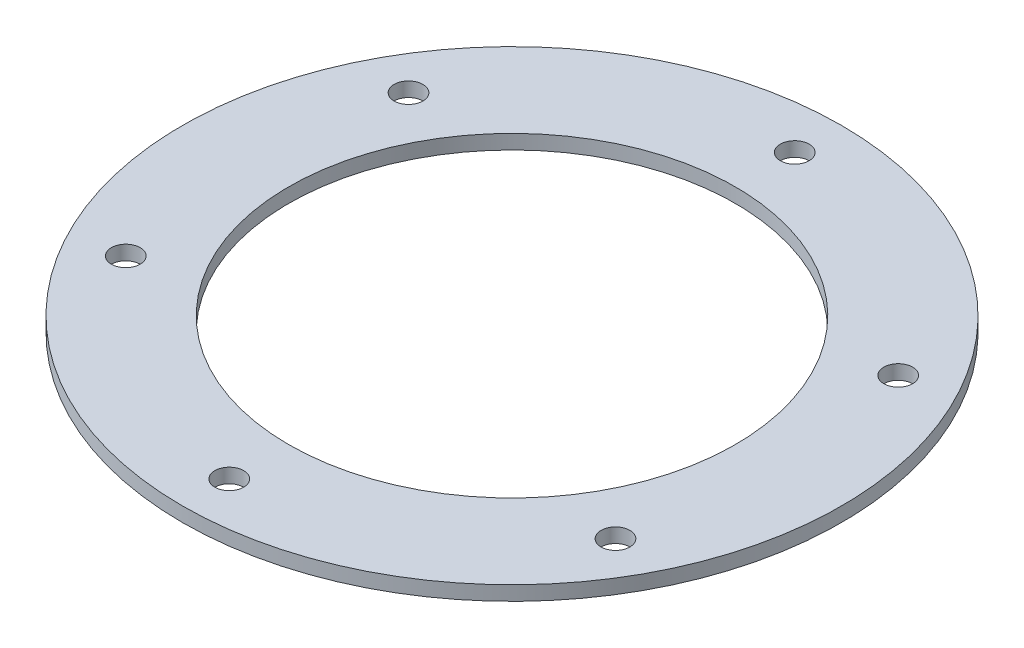
SolidWorks part; units mm, degrees
material "ABS"
ref_plane "Front Plane" through (0, 0, 0) normal (0, 0, 1) x (1, 0, 0)
ref_plane "Top Plane" through (0, 0, 0) normal (0, 1, 0) x (1, 0, 0)
ref_plane "Right Plane" through (0, 0, 0) normal (1, 0, 0) x (0, 0, -1)
sketch "Sketch1" plane through (0, 0, 0) normal (0, 1, 0) x (1, 0, 0)
  circle A0 centre (0, 0) radius 45.75
  circle A1 centre (0, 0) radius 31
  circle A2 centre (0, 0) radius 39.25 construction
  circle A3 centre (0, 39.25) radius 2
  circle A4 centre (33.9915, 19.625) radius 2
  circle A5 centre (33.9915, -19.625) radius 2
  circle A6 centre (0, -39.25) radius 2
  circle A7 centre (-33.9915, -19.625) radius 2
  circle A8 centre (-33.9915, 19.625) radius 2
  point P19 (0, 0)
  dimension "D1" = 91.5
  dimension "D2" = 62
  dimension "D3" = 78.5
  dimension "D4" = 4
  dimension "D5" = 6
extrude "Boss-Extrude1" add sketch "Sketch1" against normal mid plane 2
equation "\"Ns\" = 33"
equation "\"Np\" = 45"
equation "\"Nr\" = 123"
equation "\"num_planet\" = 3"
equation "\"module\" = 0.5"
equation "\"pressure angle\" = 20.0"
equation "\"motor_mount_hole_PCD\" = 32"
equation "\"motor_mount_hole_dia\" = 4"
equation "\"motor_mount_hole_num\" = 4"
equation "\"motor_output_hole_PCD\" = 22"
equation "\"motor_output_hole_dia\" = 3"
equation "\"motor_output_hole_num\" = 4"
equation "\"motor_OD\" = 72"
equation "\"motor_height\" = 27"
equation "\"wire_slot_dist_from_center\" = 30"
equation "\"wire_slot_length\" = 10"
equation "\"wire_slot_radius\" = 2.5"
equation "\"h_a\" = 0.5"
equation "\"h_b\" = 0.625"
equation "\"clr_tip_root\" = 0.125"
equation "\"dp_s\" = 16.5"
equation "\"db_s\" = 15.50492824296749"
equation "\"fw_s_calc\" = 1.2595130854287364"
equation "\"alpha_s\" = 0.8539582918412449"
equation "\"beta_s\" = 3.7466288708629643"
equation "\"dp_p\" = 22.5"
equation "\"db_p\" = 21.14308396768294"
equation "\"fw_p\" = 8.0"
equation "\"alpha_p\" = 0.8539582918412307"
equation "\"beta_p\" = 2.2920834163175385"
equation "\"pressure_angle\" = 20.0"
equation "\"h_f\" = 0.625"
equation "\"dp_r\" = 61.5"
equation "\"db_r\" = 57.79109617833337"
equation "\"fw_r\" = 8.0"
equation "\"alpha_r\" = 0.8539582918412414"
equation "\"beta_r\" = 3.171331217828824"
equation "\"bearing_ID\" = 50"
equation "\"bearing_OD\" = 65"
equation "\"bearing_height\" = 7"
equation "\"clearance_planet\" = 1.5"
equation "\"case_dist\" = 6.5"
equation "\"Motor_case_OD_max\" = 96.5"
equation "\"case_mounting_PCD\" = 89.0"
equation "\"bearing mount thickness\" = 8"
equation "\"case_mounting_hole_dia\" = 3"
equation "\"output_mounting_PCD\" = 73"
equation "\"output_mounting_hole_dia\" = 4"
equation "\"clearance_case_mount_holes_shell_thickness\" = 1"
equation "\"motor_case_OD_base\" = 87.0"
equation "\"sec_carrier_thickness\" = 5"
equation "\"sun_coupler_hub_thickness\" = 4"
equation "\"clearance_sun_coupler_sec_carrier\" = 1.5"
equation "\"clearance_motor_and_case\" = 5"
equation "\"Motor_case_thickness\" = 2.5"
equation "\"Motor_case_ID\" = 82"
equation "\"case_mounting_hole_shift\" = 1.0"
equation "\"output_mounting_nut_wrench_size\" = 7"
equation "\"output_mounting_nut_thickness\" = 3.2"
equation "\"case_mounting_hole_allen_socket_dia\" = 5.5"
equation "\"output_mounting_nut_depth\" = 3"
equation "\"case_mounting_bolt_depth\" = 4.5"
equation "\"ring_radial_thickness\" = 5"
equation "\"ring_OD\" = 71.5"
equation "\"ring_to_chamfer_clearance\" = 2"
equation "\"Motor_case_OD_base_to_chamfer\" = 5"
equation "\"pattern_offset_from_motor_case_OD_base\" = 3"
equation "\"pattern_bulge_dia\" = 3"
equation "\"pattern_num_bulge\" = 18"
equation "\"pattern_depth\" = 2"
equation "\"case_mounting_wrench_size\" = 5.5"
equation "\"case_mounting_nut_clearance\" = 2"
equation "\"base_plate_thickness\" = 4"
equation "\"case_mounting_nut_thickness\" = 2.4"
equation "\"case_mounting_surface_height\" = 4"
equation "\"central_hole_offset_from_motor_mount_PCD\" = 5"
equation "\"driver_upper_holes_dist_from_center\" = 23"
equation "\"driver_lower_holes_dist_from_center\" = 15"
equation "\"driver_side_holes_dist_from_center\" = 20"
equation "\"driver_mount_holes_dia\" = 2.5"
equation "\"driver_mount_inserts_OD\" = 3.5"
equation "\"driver_mount_thickness\" = 1.5"
equation "\"driver_mount_height\" = 4"
equation "\"air_flow_hole_offset\" = 3"
equation "\"planet_pin_bolt_dia\" = 5"
equation "\"planet_pin_socket_head_dia\" = 8.5"
equation "\"carrier_PCD\" = 39.0"
equation "\"planet_shaft_dia\" = 8"
equation "\"planet_shaft_step_offset\" = 1"
equation "\"carrier_trapezoidal_support_sun_offset\" = 5"
equation "\"carrier_trapezoidal_support_hole_PCD_offset_bearing_ID\" = 4"
equation "\"carrier_trapezoidal_support_hole_dia\" = 3"
equation "\"carrier_trapezoidal_support_hole_socket_head_dia\" = 5.5"
equation "\"carrier_bearing_step_width\" = 1.5"
equation "\"standard_clearance_1_5mm\" = 1.5"
equation "\"standard_fillet_1_5mm\" = 1.5"
equation "\"sun_shaft_bearing_OD\" = 16"
equation "\"sun_shaft_bearing_width\" = 5"
equation "\"standard_bearing_insertion_chamfer\" = 0.5"
equation "\"carrier_trapezoidal_support_hole_wrench_size\" = 5.5"
equation "\"planet_pin_bolt_wrench_size\" = 8"
equation "\"planet_bearing_OD\" = 12"
equation "\"planet_bearing_width\" = 3.5"
equation "\"planet_bore\" = 10"
equation "\"sun_shaft_bearing_ID\" = 8"
equation "\"sun_hub_dia\" = 31.0"
equation "\"sun_central_bolt_dia\" = 5"
equation "\"sun_central_bolt_socket_head_dia\" = 8.5"
equation "\"fw_s_used\" = 16.0"
equation "\"motor_output_hole_CSK_OD\" = 6"
equation "\"motor_output_hole_CSK_head_height\" = 1.5"
equation "\"bearing_retainer_thickness\" = 2"
equation "\"stg1_stg2_mounting_pattern_width\" = 12"
equation "\"stg1_stg2_allen_socket_head_dia\" = 7.0"
equation "\"stg1_stg2_mounting_hole_dia\" = 4"
equation "\"stg1_carrier_stg2_sun_coupling_pcd\"= 20"
equation "\"stg1_carrier_stg2_sun_coupling_dia\"= 4"
equation "\"stg1_carrier_stg2_sun_coupling_nut_wrench\"= 7"
equation "\"stg1_carrier_stg2_sun_coupling_num\"= 3"
equation "\"stg1_carrier_stg2_sun_coupling_nut_thickness\"= 3.2"
equation "\"Ns2\" = 33"
equation "\"Np2\" = 45"
equation "\"Nr2\" = 123"
equation "\"module2\" = 0.5"
equation "\"stg1_stg2_mounting_extra_width\" = 5.25"
equation "\"dp_s2\" = 16.5"
equation "\"db_s2\" = 15.50492824296749"
equation "\"fw_s_calc2\" = 5.95406185839039"
equation "\"alpha_s2\" = 0.8539582918412449"
equation "\"beta_s2\" = 3.7466288708629643"
equation "\"fw_s_used2\" = 16.0"
equation "\"fw_p2\" = 8.0"
equation "\"D1@Sketch1\"=\"bearing_OD\" + \"bearing mount thickness\" * 2 + \"stg1_stg2_mounting_extra_width\"*2"
equation "\"D2@Sketch1\"= \"bearing_OD\" - \"standard_clearance_1_5mm\"*2"
equation "\"D3@Sketch1\"=IF( ((\"Nr2\" * \"module2\" + \"ring_radial_thickness\" * 2+ \"stg1_stg2_allen_socket_head_dia\") / 2 + \"standard_clearance_1_5mm\" * 2 + \"stg1_stg2_allen_socket_head_dia\" / 2) > ((\"bearing_OD\" + \"bearing mount thickness\" * 2) / 2), \"Nr2\" * \"module2\" + \"ring_radial_thickness\" * 2 + \"stg1_stg2_allen_socket_head_dia\", \"output_mounting_PCD\" )"
equation "\"D4@Sketch1\"=\"stg1_stg2_mounting_hole_dia\""
equation "\"D1@Boss-Extrude1\"=\"bearing_retainer_thickness\""
